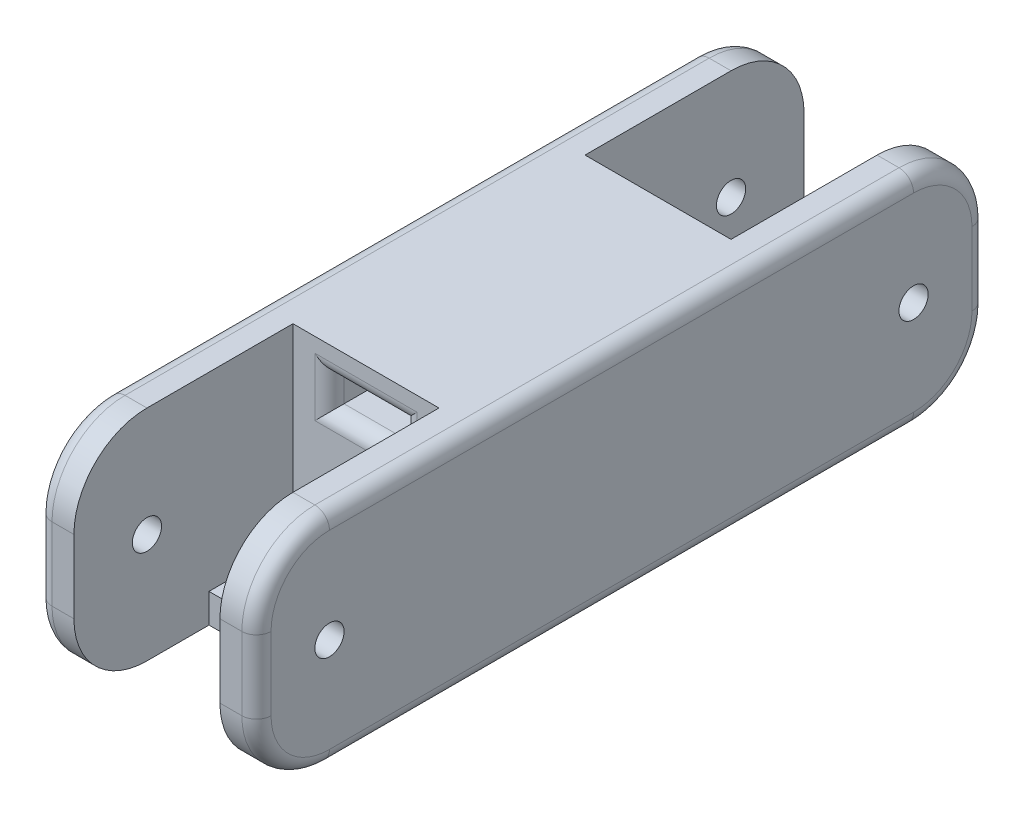
SolidWorks part; units mm, degrees
ref_plane "Front Plane" through (0, 0, 0) normal (0, 0, 1) x (1, 0, 0)
ref_plane "Top Plane" through (0, 0, 0) normal (0, 1, 0) x (1, 0, 0)
ref_plane "Right Plane" through (0, 0, 0) normal (1, 0, 0) x (0, 0, -1)
sketch "Bottom Section Base Sketch" plane through (0, 0, 0) normal (0, 0, 1) x (1, 0, 0)
  line L1 (-7.5, 7.5) -> (7.5, 7.5)
  line L2 (-7.5, 7.5) -> (-7.5, -7.5)
  line L3 (-7.5, -7.5) -> (7.5, -7.5)
  line L4 (7.5, 7.5) -> (7.5, -7.5)
  line L5 (-7.5, 7.5) -> (7.5, -7.5) construction
  line L6 (-7.5, -7.5) -> (7.5, 7.5) construction
  point P0 (0, 0)
  dimension "D1" = 15
  dimension "D2" = 15
extrude "Bottom Section Extrude" add sketch "Bottom Section Base Sketch" along normal blind 50
sketch "Hinge Cutout Sketch" plane through (0, 0, 0) normal (0, 0, 1) x (1, 0, 0)
  line L1 (5, 7.5) -> (-5, 7.5)
  line L2 (5, 7.5) -> (5, -7.5)
  line L3 (5, -7.5) -> (-5, -7.5)
  line L4 (-5, 7.5) -> (-5, -7.5)
  line L5 (7.5, -7.5) -> (7.5, 7.5) construction
  line L6 (0, 0) -> (0, 10.7526) construction
  line L7 (7.5, 7.5) -> (-7.5, 7.5) construction
  line L8 (0, 0) -> (-12.6441, 0) construction
  dimension "D1" = 2.5
extrude "Hinge Cutout Extruded Cut" cut sketch "Hinge Cutout Sketch" along normal blind 15
sketch "Hinge Hole Sketch" plane through (7.5, 0, 0) normal (1, 0, 0) x (0, 0, -1)
  line L0 (0, 0) -> (-29.5332, 0) construction
  line L1 (0, -7.5) -> (0, 7.5) construction
  circle A0 centre (-5, 0) radius 1
  dimension "D1" = 2
  dimension "D2" = 5
extrude "Hinge Hole Extruded Cut" cut sketch "Hinge Hole Sketch" against normal through all
ref_plane "Part Midplane Relative to Front Plane" through (0, 0, 25) normal (0, 0, 1) x (1, 0, 0)
mirror "Hinge and Hole Cutout Mirror" about plane through (0, 0, 25) normal (0, 0, 1) of "Hinge Hole Extruded Cut", "Hinge Cutout Extruded Cut"
fillet "Hinger Corner Fillets" radius 5 8 edges at (6.25, 7.5, 50) (6.25, -7.5, 50) (-6.25, -7.5, 50) (-6.25, 7.5, 50) (-6.25, 7.5, 0) (-6.25, -7.5, 0) (6.25, -7.5, 0) (6.25, 7.5, 0)
fillet "Style Fillets" radius 1 16 edges at (7.5, 6.0355, 48.5355) (7.5, 0, 50) (7.5, -6.0355, 48.5355) (7.5, -7.5, 25) (7.5, -6.0355, 1.4645) (7.5, 0, 0) (7.5, 6.0355, 1.4645) (7.5, 7.5, 25) (-7.5, 6.0355, 48.5355) (-7.5, 0, 50) (-7.5, -6.0355, 48.5355) (-7.5, -7.5, 25) (-7.5, -6.0355, 1.4645) (-7.5, 0, 0) (-7.5, 6.0355, 1.4645) (-7.5, 7.5, 25)
sketch "Routing Holes Sketch" plane through (0, 0, 0) normal (0, 0, 1) x (1, 0, 0)
  line L0 (0, 0) -> (9.2623, 0) construction
  line L1 (0, 0) -> (0, 9.2302) construction
  line L2 (5, 7.5) -> (-5, 7.5) construction
  line L3 (-2.5, 5.5) -> (2.5, 5.5)
  line L4 (-2.5, 5.5) -> (-2.5, 3.5)
  line L5 (-2.5, 3.5) -> (2.5, 3.5)
  line L6 (2.5, 5.5) -> (2.5, 3.5)
  line L7 (2.5, -5.5) -> (2.5, -3.5)
  line L8 (-2.5, -3.5) -> (2.5, -3.5)
  line L9 (-2.5, -5.5) -> (-2.5, -3.5)
  line L10 (-2.5, -5.5) -> (2.5, -5.5)
  dimension "D1" = 2
  dimension "D2" = 2
  dimension "D3" = 5
extrude "Routing Holes Extruded Cut" cut sketch "Routing Holes Sketch" along normal through all
sketch "Backing Sketch" plane through (0, 0, 35) normal (0, 0, 1) x (1, 0, 0)
  line L0 (5, -7.5) -> (5, 7.5) construction
  line L1 (-5, -7.5) -> (5, -7.5)
  line L2 (-5, -7.5) -> (-5, -5.5)
  line L3 (-5, -5.5) -> (5, -5.5)
  line L4 (5, -7.5) -> (5, -5.5)
  line L5 (2.5, -5.5) -> (-2.5, -5.5) construction
extrude "Backing Extrude" add sketch "Backing Sketch" along normal blind 5.75
fillet "Routing Fillets" radius 1 15 edges at (2.5, 4.5, 35) (0, 5.5, 35) (-2.5, 4.5, 35) (0, 3.5, 35) (-2.5, 4.5, 15) (0, 5.5, 15) (2.5, 4.5, 15) (0, 3.5, 15) (2.5, -4.5, 35) (0, -3.5, 35) (-2.5, -4.5, 35) (2.5, -4.5, 15) (0, -3.5, 15) (-2.5, -4.5, 15) (0, -5.5, 15)
